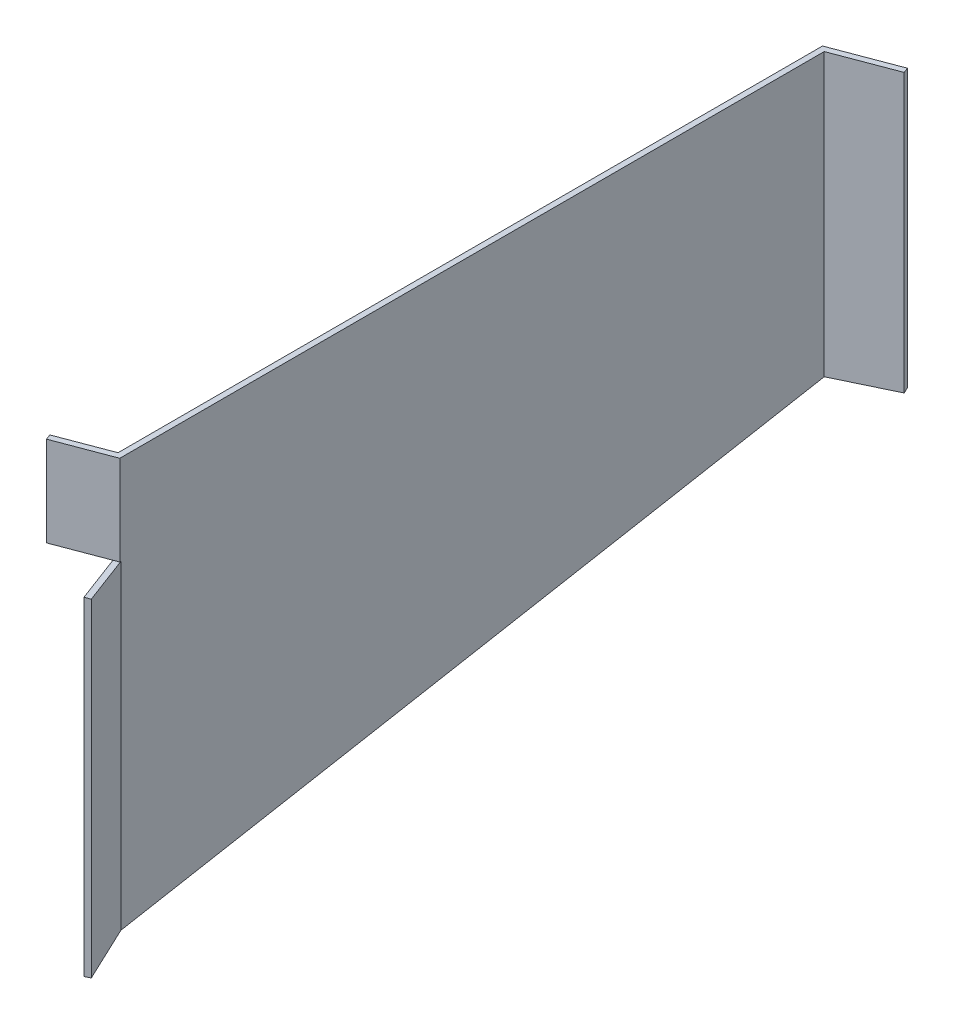
SolidWorks part; units mm, degrees
ref_plane "Front Plane" through (0, 0, 0) normal (0, 0, 1) x (1, 0, 0)
ref_plane "Top Plane" through (0, 0, 0) normal (0, 1, 0) x (1, 0, 0)
ref_plane "Right Plane" through (0, 0, 0) normal (1, 0, 0) x (0, 0, -1)
sketch "Sketch1" plane through (0, 0, 0) normal (0, 1, 0) x (1, 0, 0)
  line L1 (0, 0) -> (3.175, 0)
  line L2 (0, 0) -> (0, 395.4099)
  line L3 (0, 395.4099) -> (3.175, 395.4099)
  line L4 (3.175, 0) -> (3.175, 395.4099)
  dimension "D1" = 3.175
  dimension "D2" = 395.4099
extrude "Boss-Extrude1" add sketch "Sketch1" along normal blind 228.6
sketch "Sketch2" plane through (3.175, 0, 0) normal (1, 0, 0) x (0, 0, -1)
  line L0 (0, 0) -> (395.4099, 71.7959)
  line L1 (395.4099, 228.6) -> (395.4099, 0) construction
  line L2 (395.4099, 71.7959) -> (395.4099, 0)
  line L3 (395.4099, 0) -> (0, 0)
  dimension "D1" = 71.7959
extrude "Cut-Extrude1" cut sketch "Sketch2" against normal through all
ref_plane "Plane1" through (0, 228.6, -395.4099) normal (0, 0, 1) x (1, 0, 0)
sketch "Sketch8" plane through (0, 228.6, 0) normal (0, 1, 0) x (1, 0, 0)
  line L0 (0, 395.4099) -> (34.4591, 408.4108)
  line L1 (34.4591, 408.4108) -> (35.5798, 405.4401)
  line L2 (35.5798, 405.4401) -> (0, 392.0165)
  line L3 (0, 395.4099) -> (0, 0) construction
  line L4 (0, 392.0165) -> (0, 395.4099)
  dimension "D1" = 36.83
  dimension "D2" = 3.175
  dimension "D3" = 249.329
extrude "Boss-Extrude4" add sketch "Sketch8" against normal up to surface (157.4203 mm away)
sketch "Sketch9" plane through (0, 228.6, 0) normal (0, 1, 0) x (1, 0, 0)
  line L0 (3.175, 0) -> (-26.5311, -11.2076)
  line L1 (-26.5311, -11.2076) -> (-27.6519, -8.237)
  line L2 (-27.6519, -8.237) -> (3.175, 3.3935)
  line L3 (3.175, 0) -> (3.175, 393.2143) construction
  line L4 (3.175, 3.3935) -> (3.175, 0)
  dimension "D1" = 31.75
  dimension "D2" = 3.175
  dimension "D3" = 249.329
extrude "Boss-Extrude5" add sketch "Sketch9" against normal blind 50.165
sketch "Sketch13" plane through (0, 178.435, 0) normal (0, -1, 0) x (1, 0, 0)
  line L0 (0, 0) -> (10.192, 27.0141)
  line L1 (10.192, 27.0141) -> (13.1626, 25.8934)
  line L2 (13.1626, 25.8934) -> (1.955, -3.8127)
  line L3 (-26.5311, 11.2076) -> (3.175, 0) construction
  line L4 (1.955, -3.8127) -> (0, 0)
  dimension "D1" = 3.175
  dimension "D2" = 31.75
  dimension "D3" = 90
extrude "Boss-Extrude8" add sketch "Sketch13" along normal up to surface (177.7427 mm away)
